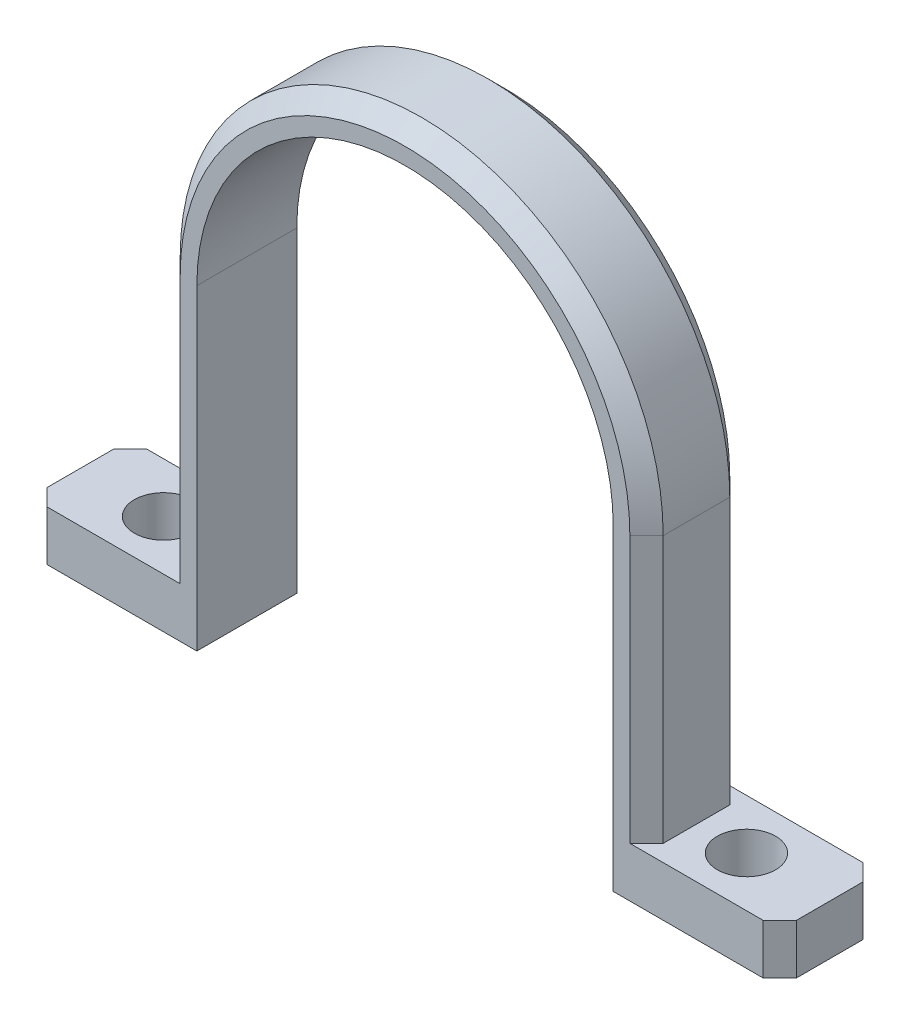
SolidWorks part; units mm, degrees
ref_plane "Front Plane" through (0, 0, 0) normal (0, 0, 1) x (1, 0, 0)
ref_plane "Top Plane" through (0, 0, 0) normal (0, 1, 0) x (1, 0, 0)
ref_plane "Right Plane" through (0, 0, 0) normal (1, 0, 0) x (0, 0, -1)
sketch "Sketch1" plane through (0, 0, 0) normal (0, 0, 1) x (1, 0, 0)
  line L0 (-14.5, 0) -> (-14.5, -16)
  line L1 (-14.5, -16) -> (-22.5, -16)
  line L2 (-22.5, -16) -> (-22.5, -19)
  line L3 (14.5, 0) -> (14.5, -16)
  line L4 (14.5, -16) -> (22.5, -16)
  line L5 (22.5, -16) -> (22.5, -19)
  line L6 (22.5, -19) -> (12.5, -19)
  line L7 (12.5, -19) -> (-12.5, -19) construction
  line L8 (-12.5, -19) -> (-22.5, -19)
  line L9 (-12.5, 0) -> (-12.5, -19)
  line L10 (12.5, 0) -> (12.5, -19)
  arc A0 (14.5, 0) -> (-14.5, 0) centre (0, 0) ccw
  arc A1 (12.5, 0) -> (-12.5, 0) centre (0, 0) ccw
  dimension "D1" = 25
  dimension "D2" = 2
  dimension "D3" = 3
  dimension "D4" = 45
  dimension "D5" = 19
extrude "Boss-Extrude1" add sketch "Sketch1" along normal blind 6
sketch "Sketch2" plane through (0, -19, 0) normal (0, -1, 0) x (1, 0, 0)
  line L0 (-17.5, 3) -> (17.5, 3) construction
  line L1 (0, 3) -> (0, 0) construction
  circle A0 centre (-17.5, 3) radius 1.75
  circle A1 centre (17.5, 3) radius 1.75
  dimension "D3" = 3.5
  dimension "D1" = 3
  dimension "D2" = 35
extrude "Cut-Extrude1" cut sketch "Sketch2" against normal through all
chamfer "Chamfer1" distance 1 angle 45 10 edges at (-14.5, -8, 0) (0, 14.5, 0) (14.5, -8, 0) (-14.5, -8, 6) (0, 14.5, 6) (14.5, -8, 6) (22.5, -17.5, 0) (22.5, -17.5, 6) (-22.5, -17.5, 0) (-22.5, -17.5, 6)
